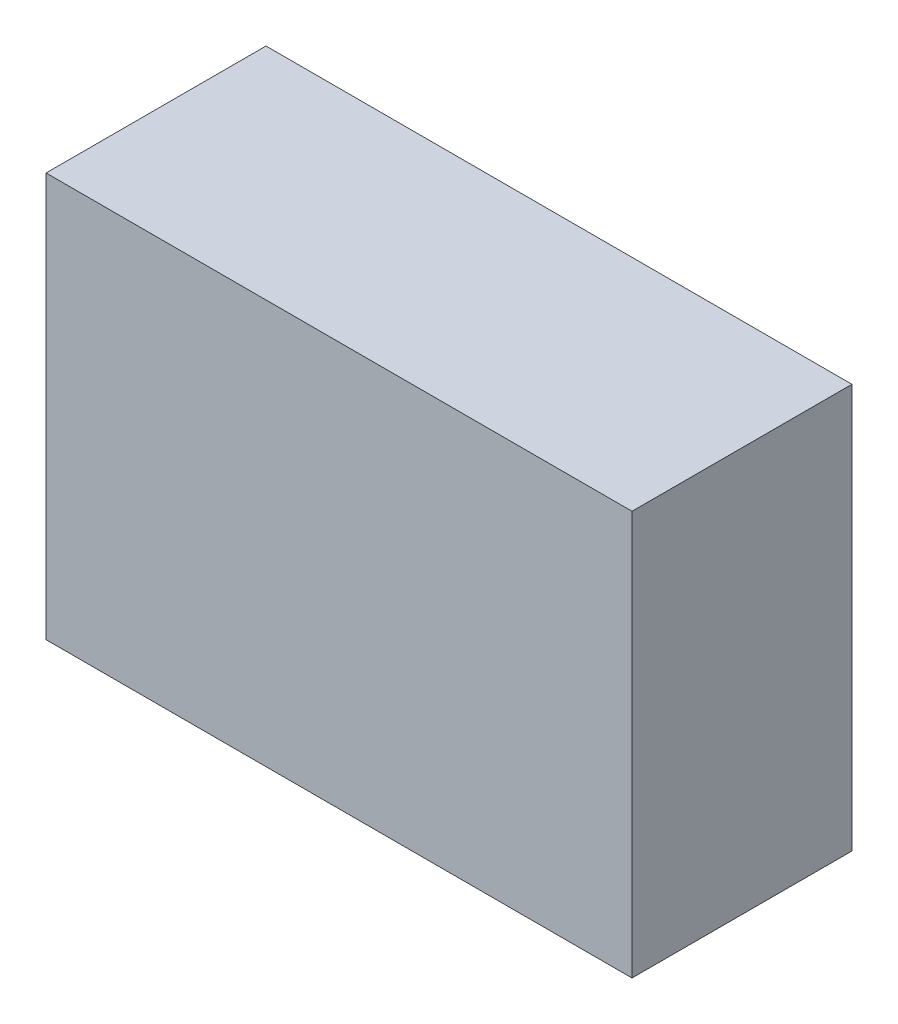
SolidWorks part; units mm, degrees
ref_plane "Front Plane" through (0, 0, 0) normal (0, 0, 1) x (1, 0, 0)
ref_plane "Top Plane" through (0, 0, 0) normal (0, 1, 0) x (1, 0, 0)
ref_plane "Right Plane" through (0, 0, 0) normal (1, 0, 0) x (0, 0, -1)
sketch "Sketch1" plane through (0, 0, 0) normal (0, 0, 1) x (1, 0, 0)
  line L1 (29.0322, 20.0279) -> (-29.0322, 20.0279)
  line L2 (29.0322, 20.0279) -> (29.0322, -20.0279)
  line L3 (29.0322, -20.0279) -> (-29.0322, -20.0279)
  line L4 (-29.0322, 20.0279) -> (-29.0322, -20.0279)
  line L5 (29.0322, 20.0279) -> (-29.0322, -20.0279) construction
  line L6 (29.0322, -20.0279) -> (-29.0322, 20.0279) construction
  point P0 (0, 0)
  dimension "D1" = 58.0644
  dimension "D2" = 40.0558
extrude "Boss-Extrude1" add sketch "Sketch1" along normal blind 21.7932
